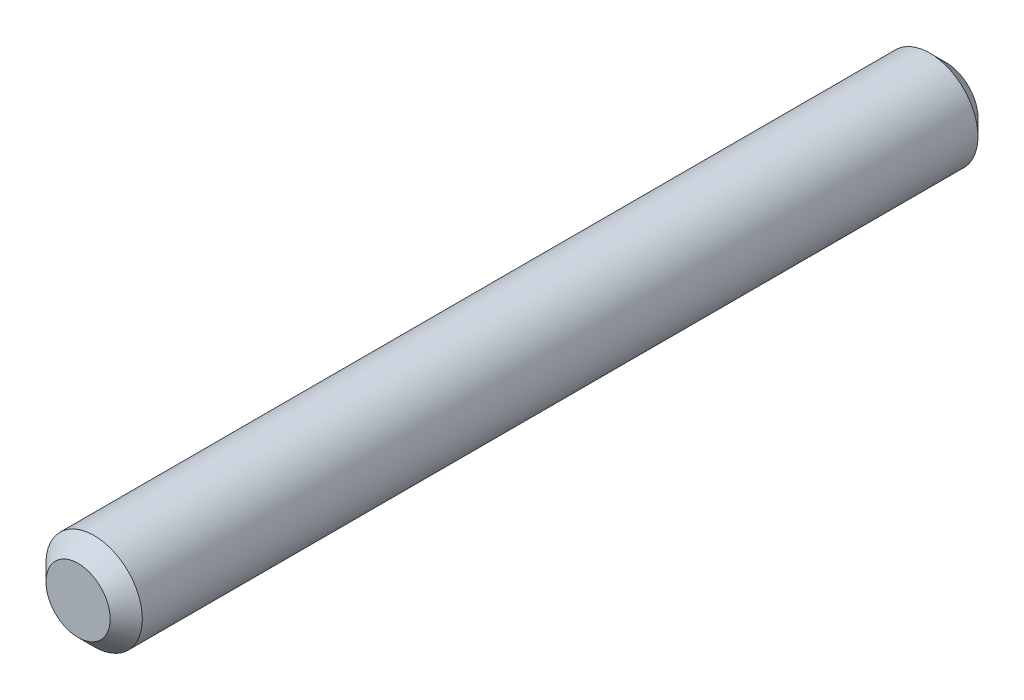
SolidWorks part; units mm, degrees
ref_plane "Front Plane" through (0, 0, 0) normal (0, 0, 1) x (1, 0, 0)
ref_plane "Top Plane" through (0, 0, 0) normal (0, 1, 0) x (1, 0, 0)
ref_plane "Right Plane" through (0, 0, 0) normal (1, 0, 0) x (0, 0, -1)
sketch "Sketch1" plane through (0, 0, 0) normal (0, 0, 1) x (1, 0, 0)
  circle A0 centre (0, 0) radius 3
  dimension "D1" = 6
extrude "Boss-Extrude1" add sketch "Sketch1" along normal blind 54
chamfer "Chamfer1" distance 1 angle 45 2 edges at (3, 0, 0) (3, 0, 54)
